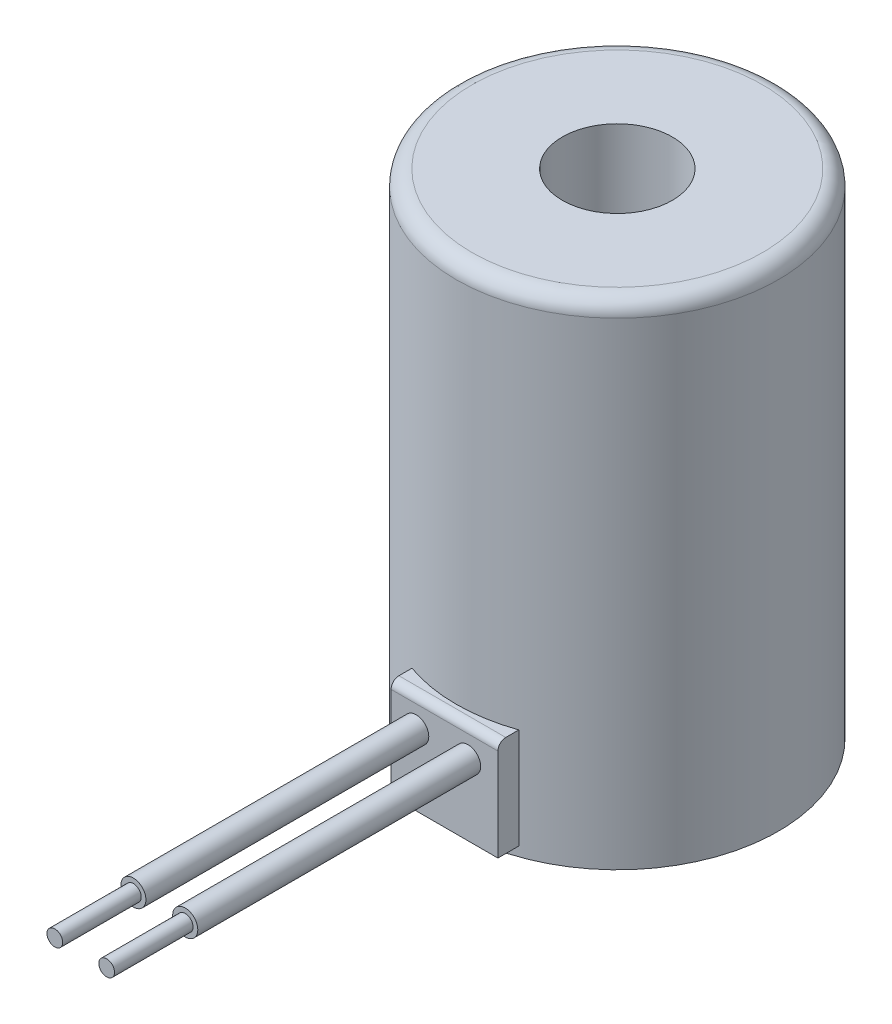
SolidWorks part; units mm, degrees
ref_plane "Front" through (0, 0, 0) normal (0, 0, 1) x (1, 0, 0)
ref_plane "Top" through (0, 0, 0) normal (0, 1, 0) x (1, 0, 0)
ref_plane "Right" through (0, 0, 0) normal (1, 0, 0) x (0, 0, -1)
sketch "Base Sketch" plane through (0, 0, 0) normal (0, 1, 0) x (1, 0, 0)
  circle A0 centre (0, 0) radius 10.25
  dimension "Dia" = 20.5
extrude "Base Extrude" add sketch "Base Sketch" along normal mid plane 31.4
fillet "Body Fillet" radius 1 1 edges at (0, 15.7, 10.25)
sketch "Wire Base Sketch" plane through (0, 0, 0) normal (0, 0, 1) x (1, 0, 0)
  line L0 (-10.25, -15.7) -> (10.25, -15.7) construction
  line L1 (-3.4, -8.7) -> (3.4, -8.7)
  line L2 (-3.4, -8.7) -> (-3.4, -15.1)
  line L3 (-3.4, -15.1) -> (3.4, -15.1)
  line L4 (3.4, -8.7) -> (3.4, -15.1)
  point P4 (0, -8.7)
  dimension "Width" = 6.8
  dimension "Height" = 6.4
  dimension "Y Edge Dist" = 0.6
extrude "Wire Base" add sketch "Wire Base Sketch" along normal blind 11
fillet "Wire Base Fillet" radius 0.5 1 edges at (0, -8.7, 11)
sketch "Wire Start Sketch" plane through (0, 0, 11) normal (0, 0, 1) x (1, 0, 0)
  line L0 (-3.4, -15.1) -> (3.4, -15.1) construction
  line L2 (-3.4, -8.7) -> (-3.4, -15.1) construction
  line L3 (3.4, -15.1) -> (3.4, -9.2) construction
  circle A0 centre (-1.8, -10.6) radius 0.8
  circle A1 centre (1.5, -10.6) radius 0.8
  dimension "Dia" = 1.6
  dimension "Y Edge Dist" = 4.5
  dimension "L X Edge Dist" = 1.6
  dimension "R X Edge Dist" = 1.9
extrude "Wire Start" add sketch "Wire Start Sketch" along normal blind 18
sketch "Wire End Sketch" plane through (0, 0, 29) normal (0, 0, 1) x (1, 0, 0)
  circle A0 centre (1.5, -10.6) radius 0.5
  circle A1 centre (-1.8, -10.6) radius 0.5
  dimension "Dia" = 1
extrude "Wire End" add sketch "Wire End Sketch" along normal blind 5
sketch "Thru Hole Sketch" plane through (0, 15.7, 0) normal (0, 1, 0) x (1, 0, 0)
  circle A0 centre (0, 0) radius 3.5
  dimension "Dia" = 7
extrude "Thru Hole" cut sketch "Thru Hole Sketch" against normal through all
